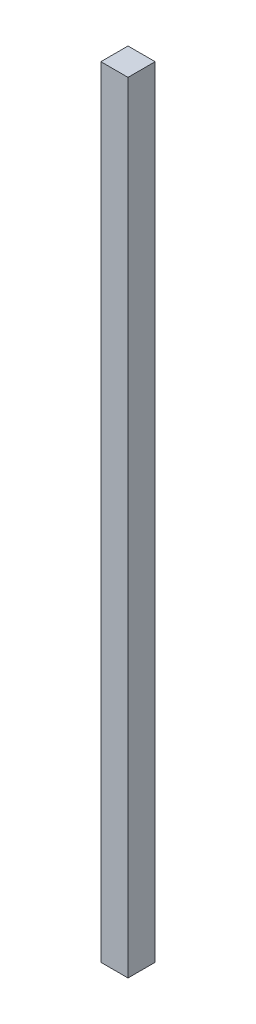
SolidWorks part; units mm, degrees
material "AISI 1035 Acero (SS)"
ref_plane "Alzado" through (0, 0, 0) normal (0, 0, 1) x (1, 0, 0)
ref_plane "Planta" through (0, 0, 0) normal (0, 1, 0) x (1, 0, 0)
ref_plane "Vista lateral" through (0, 0, 0) normal (1, 0, 0) x (0, 0, -1)
sketch "Croquis1" plane through (0, 0, 0) normal (0, 1, 0) x (1, 0, 0)
  line L1 (10, 10) -> (-10, 10)
  line L2 (10, 10) -> (10, -10)
  line L3 (10, -10) -> (-10, -10)
  line L4 (-10, 10) -> (-10, -10)
  line L5 (10, 10) -> (-10, -10) construction
  line L6 (10, -10) -> (-10, 10) construction
  point P0 (0, 0)
  dimension "D1" = 20
extrude "Saliente-Extruir1" add sketch "Croquis1" along normal blind 574.6
